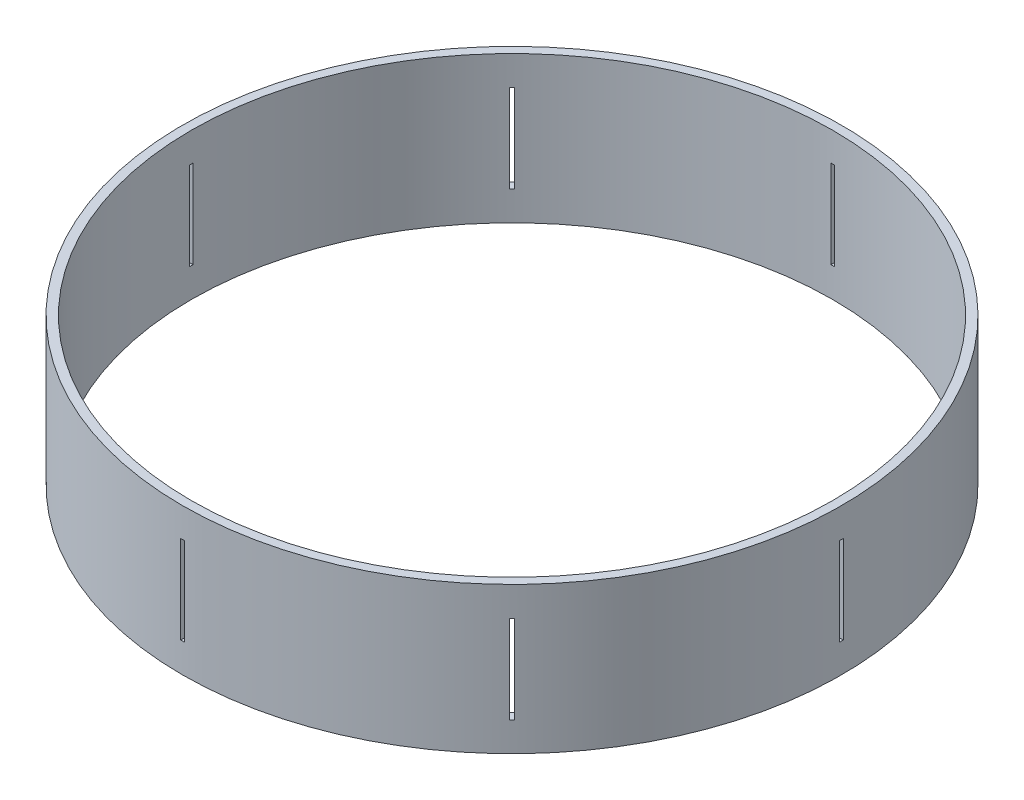
SolidWorks part; units mm, degrees
material "Thornel P30"
ref_plane "Front Plane" through (0, 0, 0) normal (0, 0, 1) x (1, 0, 0)
ref_plane "Top Plane" through (0, 0, 0) normal (0, 1, 0) x (1, 0, 0)
ref_plane "Right Plane" through (0, 0, 0) normal (1, 0, 0) x (0, 0, -1)
sketch "Sketch1" plane through (0, 0, 0) normal (0, 0, 1) x (1, 0, 0)
  line L0 (0, 0) -> (0, -104.8247) construction
  line L1 (138.9062, 192.9517) -> (142.7163, 192.9517)
  line L2 (138.9062, 192.9517) -> (138.9062, 129.4517)
  line L3 (138.9062, 129.4517) -> (142.7163, 129.4517)
  line L4 (142.7163, 192.9517) -> (142.7163, 129.4517)
  line L5 (0, -164.1944) -> (0, 164.1944)
  point P10 (0, 0)
  dimension "D1" = 142.7163
  dimension "D2" = 3.81
  dimension "D3" = 63.5
revolve "Revolve1" add sketch "Sketch1" angle 360 about L0
sketch "Sketch2" plane through (0, 0, 0) normal (1, 0, 0) x (0, 0, -1)
  line L0 (-142.7163, 129.4517) -> (142.7163, 129.4517) construction
  line L1 (-0.762, 180.2517) -> (0.762, 180.2517)
  line L2 (-0.762, 180.2517) -> (-0.762, 142.1517)
  line L3 (-0.762, 142.1517) -> (0.762, 142.1517)
  line L4 (0.762, 180.2517) -> (0.762, 142.1517)
  line L5 (142.7163, 192.9517) -> (-142.7163, 192.9517) construction
  point P8 (0, 180.2517)
  dimension "D1" = 1.524
  dimension "D2" = 12.7
  dimension "D3" = 12.7
extrude "Cut-Extrude1" cut sketch "Sketch2" against normal up to surface and the other way up to surface up to face at (0, 129.4517, 142.7163) other way up to face at (0, 129.4517, 142.7163)
pattern_circular "CirPattern1" count 4 every 45 about axis through (0, 0, 0) along (0, 1, 0) of "Cut-Extrude1"
